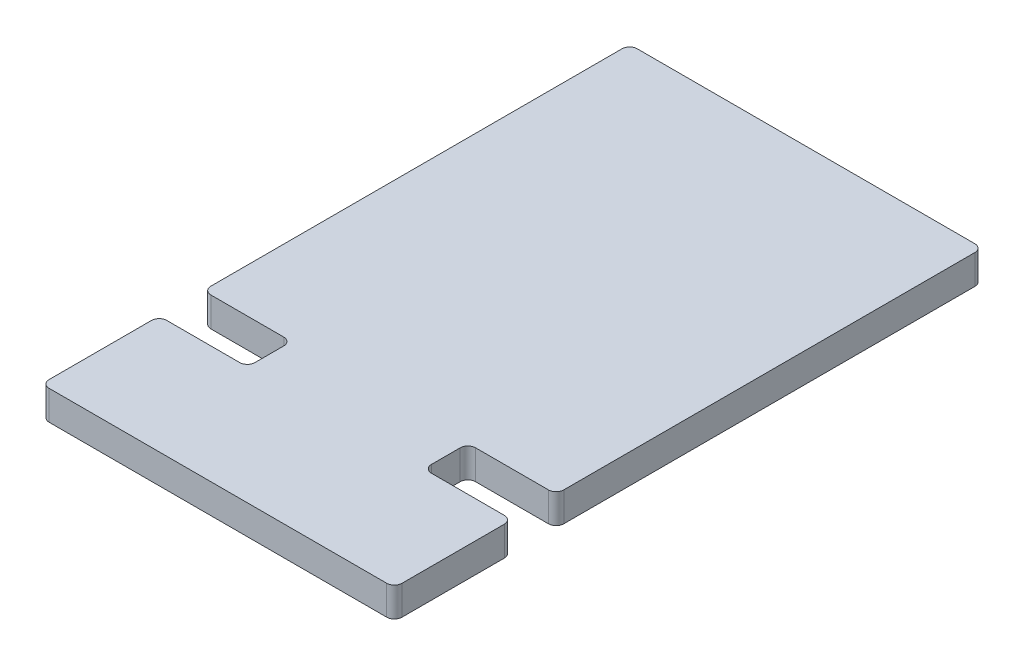
SolidWorks part; units mm, degrees
material "AISI 1020"
ref_plane "Front Plane" through (0, 0, 0) normal (0, 0, 1) x (1, 0, 0)
ref_plane "Top Plane" through (0, 0, 0) normal (0, 1, 0) x (1, 0, 0)
ref_plane "Right Plane" through (0, 0, 0) normal (1, 0, 0) x (0, 0, -1)
sketch "Sketch1" plane through (0, 0, 0) normal (0, 1, 0) x (1, 0, 0)
  line L1 (-76.2, -127) -> (76.2, -127)
  line L2 (-76.2, -127) -> (-76.2, 127)
  line L3 (-76.2, 127) -> (76.2, 127)
  line L4 (76.2, -127) -> (76.2, 127)
  line L5 (-76.2, -127) -> (76.2, 127) construction
  line L6 (-76.2, 127) -> (76.2, -127) construction
  point P0 (0, 0)
  dimension "D1" = 152.4
  dimension "D2" = 254
extrude "Boss-Extrude1" add sketch "Sketch1" along normal blind 12.7
sketch "Sketch2" plane through (0, 12.7, 0) normal (0, 1, 0) x (1, 0, 0)
  line L0 (76.2, -127) -> (76.2, 127) construction
  line L1 (76.2, -57.15) -> (38.1, -57.15)
  line L2 (76.2, -57.15) -> (76.2, -76.2)
  line L3 (76.2, -76.2) -> (38.1, -76.2)
  line L4 (38.1, -57.15) -> (38.1, -76.2)
  line L5 (-76.2, -127) -> (76.2, -127) construction
  dimension "D1" = 19.05
  dimension "D2" = 38.1
  dimension "D3" = 50.8
extrude "Cut-Extrude1" cut sketch "Sketch2" against normal through all
fillet "Fillet1" radius 3.302 2 edges at (38.1, 6.35, 76.2) (38.1, 6.35, 57.15)
mirror "Mirror1" about plane through (0, 0, 0) normal (1, 0, 0) of "Cut-Extrude1", "Fillet1"
fillet "Fillet2" radius 3.302 8 edges at (76.2, 6.35, 127) (76.2, 6.35, 76.2) (-76.2, 6.35, 127) (-76.2, 6.35, 76.2) (76.2, 6.35, 57.15) (-76.2, 6.35, 57.15) (76.2, 6.35, -127) (-76.2, 6.35, -127)
